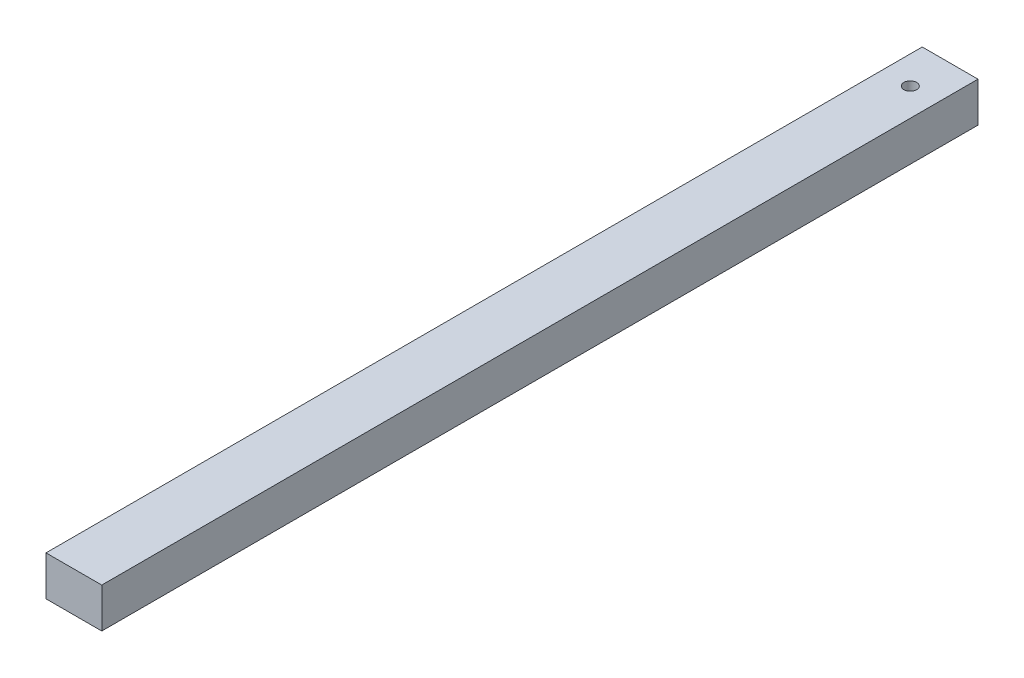
SolidWorks part; units mm, degrees
material "Beech"
ref_plane "Front Plane" through (0, 0, 0) normal (0, 0, 1) x (1, 0, 0)
ref_plane "Top Plane" through (0, 0, 0) normal (0, 1, 0) x (1, 0, 0)
ref_plane "Right Plane" through (0, 0, 0) normal (1, 0, 0) x (0, 0, -1)
sketch "Sketch2" plane through (0, 0, 0) normal (0, 0, 1) x (1, 0, 0)
  line L1 (-17.5, 12.5) -> (17.5, 12.5)
  line L2 (-17.5, 12.5) -> (-17.5, -12.5)
  line L3 (-17.5, -12.5) -> (17.5, -12.5)
  line L4 (17.5, 12.5) -> (17.5, -12.5)
  line L5 (-17.5, 12.5) -> (17.5, -12.5) construction
  line L6 (-17.5, -12.5) -> (17.5, 12.5) construction
  point P0 (0, 0)
  dimension "D1" = 35
  dimension "D2" = 25
extrude "Boss-Extrude1" add sketch "Sketch2" along normal blind 550
sketch "Sketch3" plane through (0, 12.5, 0) normal (0, 1, 0) x (1, 0, 0)
  line L0 (0, 0) -> (0, -25) construction
  circle A0 centre (0, -25) radius 4
  dimension "D2" = 8
  dimension "D1" = 25
extrude "Cut-Extrude2" cut sketch "Sketch3" against normal through all
